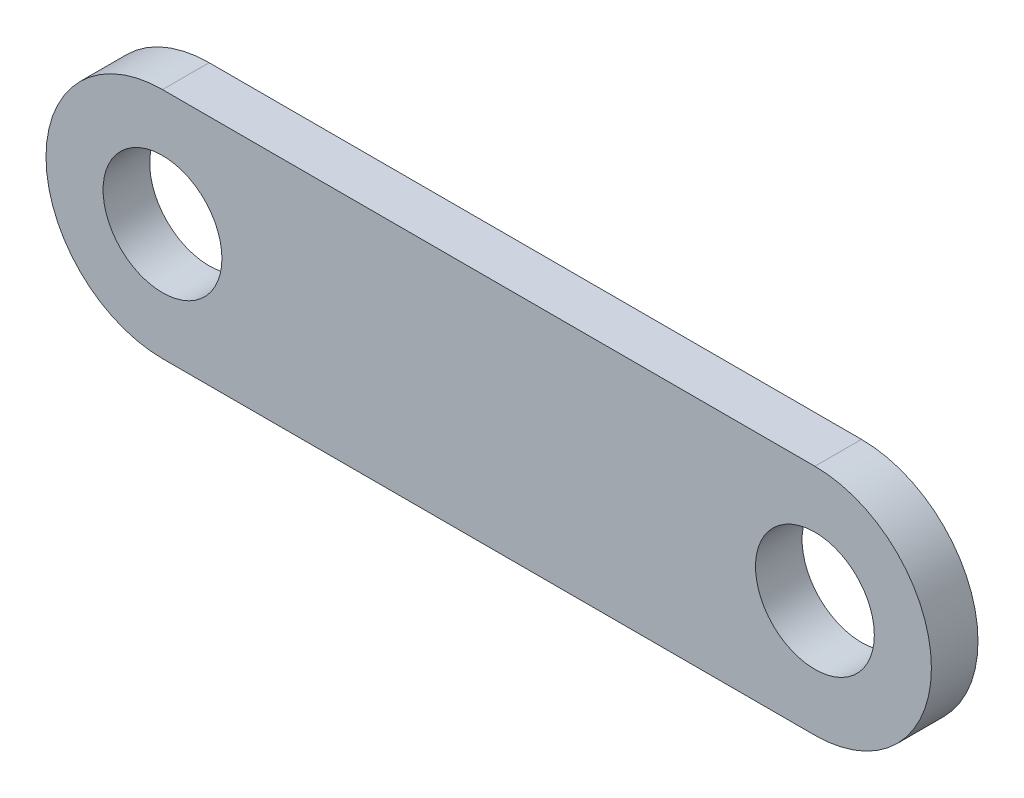
SolidWorks part; units mm, degrees
material "Thornel Mat VMA"
ref_plane "前视基准面" through (0, 0, 0) normal (0, 0, 1) x (1, 0, 0)
ref_plane "上视基准面" through (0, 0, 0) normal (0, 1, 0) x (1, 0, 0)
ref_plane "右视基准面" through (0, 0, 0) normal (1, 0, 0) x (0, 0, -1)
sketch "草图1" plane through (0, 0, 0) normal (0, 0, 1) x (1, 0, 0)
  line L0 (-14, 0) -> (14, 0) construction
  line L1 (-14, 5) -> (14, 5)
  line L2 (-14, -5) -> (14, -5)
  arc A0 (-14, 5) -> (-14, -5) centre (-14, 0) ccw
  arc A1 (14, -5) -> (14, 5) centre (14, 0) ccw
  circle A2 centre (-14, 0) radius 2.55
  circle A3 centre (14, 0) radius 2.55
  point P2 (0, 0)
  dimension "D2" = 5
  dimension "D3" = 5.1
  dimension "D1" = 28
extrude "凸台-拉伸1" add sketch "草图1" along normal blind 2
